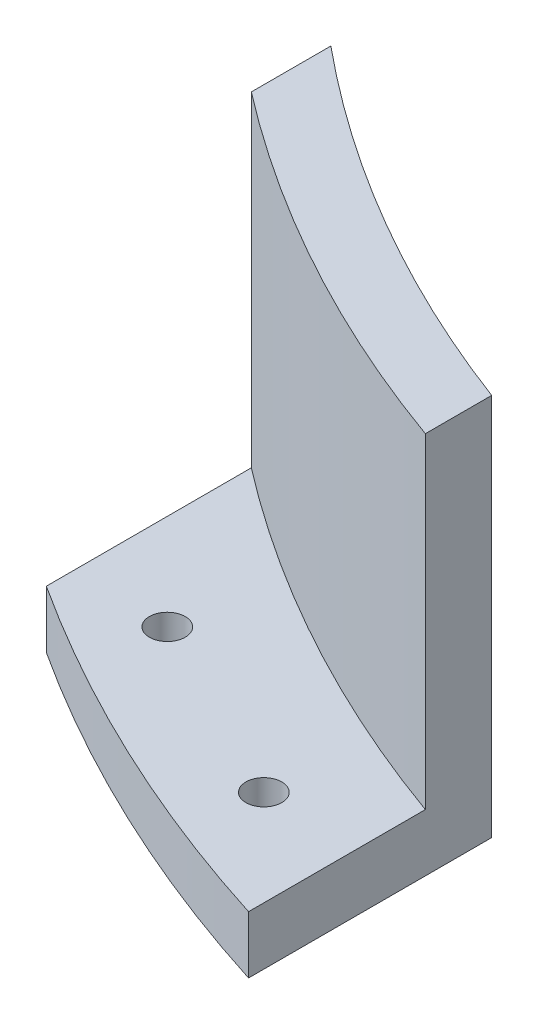
SolidWorks part; units mm, degrees
ref_plane "Front Plane" through (0, 0, 0) normal (0, 0, 1) x (1, 0, 0)
ref_plane "Top Plane" through (0, 0, 0) normal (0, 1, 0) x (1, 0, 0)
ref_plane "Right Plane" through (0, 0, 0) normal (1, 0, 0) x (0, 0, -1)
sketch "Sketch1" plane through (0, 0, 0) normal (0, 1, 0) x (1, 0, 0)
  line L0 (-63.2337, -167.5338) -> (-63.2337, -199.7816)
  line L1 (-114.0337, -138.0666) -> (-114.0337, -175.8053)
  circle A0 centre (0, 0) radius 179.07
  circle A1 centre (0, 0) radius 209.55
  dimension "D1" = 358.14
  dimension "D2" = 419.1
  dimension "D3" = 50.8
extrude "Boss-Extrude1" add sketch "Sketch1" along normal blind 50.8 contours L1 A1 L0 A0
sketch "Sketch2" plane through (0, 50.8, 0) normal (0, 1, 0) x (1, 0, 0)
  circle A0 centre (0, 0) radius 187.325
  circle A1 centre (0, 0) radius 209.55
  dimension "D1" = 374.65
extrude "Cut-Extrude1" cut sketch "Sketch2" against normal blind 43.18
sketch "Sketch3" plane through (0, 7.62, 0) normal (0, 1, 0) x (1, 0, 0)
  line L0 (-63.2337, -176.3297) -> (-63.2337, -199.7816) construction
  line L1 (-114.0337, -148.6168) -> (-114.0337, -175.8053) construction
  circle A0 centre (-101.3337, -172.4572) radius 2.3813
  circle A1 centre (-75.9337, -185.0515) radius 2.3813
  circle A2 centre (0, 0) radius 200.025 construction
  point P11 (0, 0)
  dimension "D1" = 4.7625
  dimension "D2" = 4.7625
  dimension "D5" = 400.05
  dimension "D3" = 12.7
  dimension "D4" = 12.7
extrude "Cut-Extrude2" cut sketch "Sketch3" against normal blind 43.18
